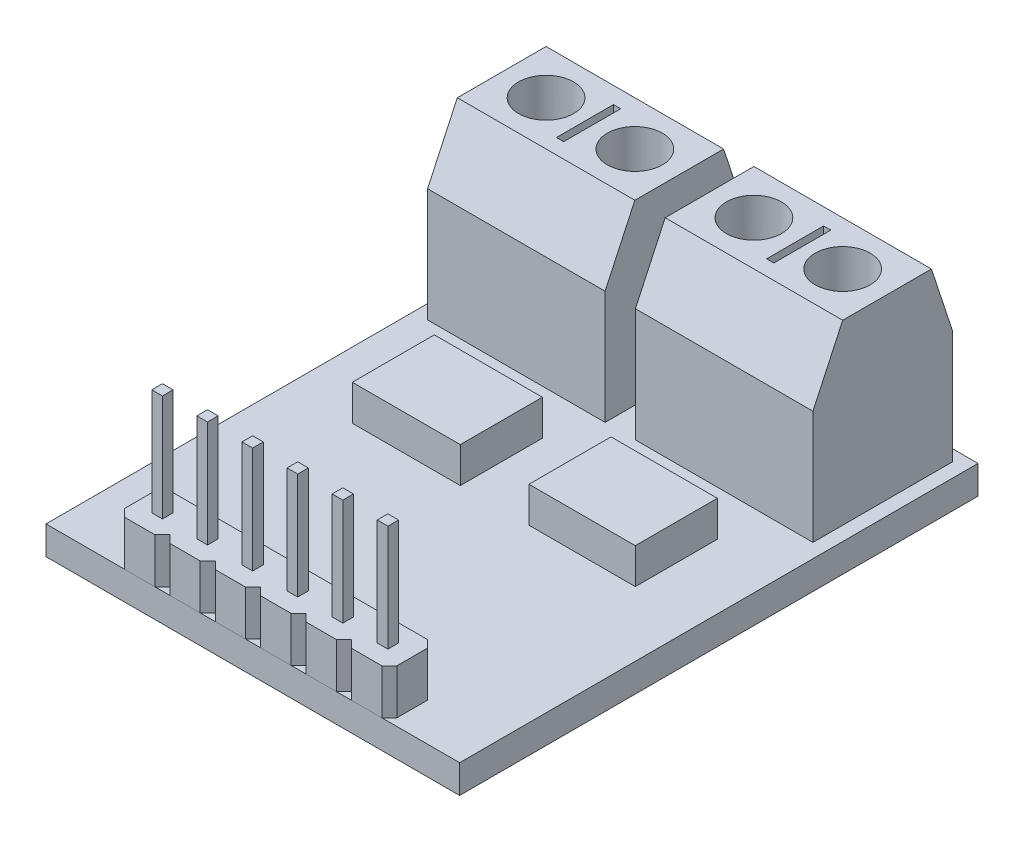
SolidWorks part; units mm, degrees
ref_plane "前视基准面" through (0, 0, 0) normal (0, 0, 1) x (1, 0, 0)
ref_plane "上视基准面" through (0, 0, 0) normal (0, 1, 0) x (1, 0, 0)
ref_plane "右视基准面" through (0, 0, 0) normal (1, 0, 0) x (0, 0, -1)
sketch "草图1" plane through (0, 0, 0) normal (0, 1, 0) x (1, 0, 0)
  line L0 (-11.65, 14.6) -> (-11.65, -14.6)
  line L1 (-11.65, 14.6) -> (11.65, 14.6)
  line L2 (-11.65, -14.6) -> (11.65, -14.6)
  line L3 (11.65, 14.6) -> (11.65, -14.6)
  line L4 (-11.65, 14.6) -> (11.65, -14.6) construction
  line L5 (-11.65, -14.6) -> (11.65, 14.6) construction
  point P1 (0, 0)
  dimension "D1" = 23.3
  dimension "D2" = 29.2
extrude "凸台-拉伸1" add sketch "草图1" along normal blind 1.6
sketch "草图2" plane through (0, 1.6, 0) normal (0, 1, 0) x (1, 0, 0)
  line L0 (0, -21.513) -> (0, -14.1561) construction
  line L1 (-4.6683, -12.0374) -> (-2.9595, -12.0374)
  line L2 (-7.2257, -12.0374) -> (-5.5169, -12.0374)
  line L3 (-7.65, -12.4617) -> (-7.65, -14.1783)
  line L4 (-7.2257, -14.6026) -> (-5.5169, -14.6026)
  line L6 (-11.65, 14.6) -> (-11.65, -14.6) construction
  line L7 (-7.2257, -12.0374) -> (-7.65, -12.4617)
  line L8 (-8.7149, -13.32) -> (-4.2245, -13.32) construction
  line L9 (-6.3713, -11.2945) -> (-6.3713, -15.2716) construction
  line L10 (-7.2257, -14.6026) -> (-7.65, -14.1783)
  line L11 (-5.5169, -14.6026) -> (-5.0926, -14.1783)
  line L12 (-5.5169, -12.0374) -> (-5.0926, -12.4617)
  line L14 (-2.9595, -12.0374) -> (-2.5352, -12.4617)
  line L15 (-2.9595, -14.6026) -> (-2.5352, -14.1783)
  line L16 (-4.6683, -14.6026) -> (-2.9595, -14.6026)
  line L17 (-4.6683, -14.6026) -> (-5.0926, -14.1783)
  line L19 (-4.6683, -12.0374) -> (-5.0926, -12.4617)
  line L20 (-2.1109, -12.0374) -> (-0.4021, -12.0374)
  line L22 (-0.4021, -12.0374) -> (0.0222, -12.4617)
  line L23 (-0.4021, -14.6026) -> (0.0222, -14.1783)
  line L24 (-2.1109, -14.6026) -> (-0.4021, -14.6026)
  line L25 (-2.1109, -14.6026) -> (-2.5352, -14.1783)
  line L27 (-2.1109, -12.0374) -> (-2.5352, -12.4617)
  line L28 (0.4465, -12.0374) -> (2.1553, -12.0374)
  line L30 (2.1553, -12.0374) -> (2.5796, -12.4617)
  line L31 (2.1553, -14.6026) -> (2.5796, -14.1783)
  line L32 (0.4465, -14.6026) -> (2.1553, -14.6026)
  line L33 (0.4465, -14.6026) -> (0.0222, -14.1783)
  line L35 (0.4465, -12.0374) -> (0.0222, -12.4617)
  line L36 (3.0039, -12.0374) -> (4.7127, -12.0374)
  line L38 (4.7127, -12.0374) -> (5.137, -12.4617)
  line L39 (4.7127, -14.6026) -> (5.137, -14.1783)
  line L40 (3.0039, -14.6026) -> (4.7127, -14.6026)
  line L41 (3.0039, -14.6026) -> (2.5796, -14.1783)
  line L43 (3.0039, -12.0374) -> (2.5796, -12.4617)
  line L44 (5.5613, -12.0374) -> (7.2701, -12.0374)
  line L45 (7.6944, -12.4617) -> (7.6944, -14.1783)
  line L46 (7.2701, -12.0374) -> (7.6944, -12.4617)
  line L47 (7.2701, -14.6026) -> (7.6944, -14.1783)
  line L48 (5.5613, -14.6026) -> (7.2701, -14.6026)
  line L49 (5.5613, -14.6026) -> (5.137, -14.1783)
  line L51 (5.5613, -12.0374) -> (5.137, -12.4617)
  line L52 (-2.5352, -12.4617) -> (-2.5352, -14.1783) [skipped]
  line L54 (0.0222, -12.4617) -> (0.0222, -14.1783) [skipped]
  line L56 (0, -12.4839) -> (0, -10.5331) construction
  line L57 (2.5796, -12.4617) -> (2.5796, -14.1783) [skipped]
  line L59 (5.137, -12.4617) -> (5.137, -14.1783) [skipped]
  line L61 (-5.0926, -12.4643) -> (-5.0926, -13.32) [skipped]
  point P3 (-5.0897, -14.1788)
  dimension "D1" = 6
  dimension "D3" = 4
  dimension "D4" = 0.6
  dimension "D5" = 135
extrude "凸台-拉伸2" add sketch "草图2" along normal blind 2.54
sketch "草图3" plane through (0, 4.14, 0) normal (0, 1, 0) x (1, 0, 0)
  line L1 (-6.6713, -13.02) -> (-6.0713, -13.02)
  line L2 (-6.6713, -13.02) -> (-6.6713, -13.62)
  line L3 (-6.6713, -13.62) -> (-6.0713, -13.62)
  line L4 (-6.0713, -13.02) -> (-6.0713, -13.62)
  line L5 (-6.3713, -11.7173) -> (-6.3713, -15.4153) construction
  line L6 (-8.2029, -13.32) -> (-4.4774, -13.32) construction
  line L7 (-5.5169, -12.0374) -> (-7.2257, -12.0374) construction
  line L8 (-7.2257, -14.6026) -> (-5.5169, -14.6026) construction
  line L9 (-7.65, -12.4617) -> (-7.65, -14.1783) construction
  dimension "D1" = 0.6
  dimension "D2" = 0.6
  dimension "D3" = 0.9787
extrude "凸台-拉伸3" add sketch "草图3" along normal blind 6
pattern_linear "阵列(线性)11" count 6 spacing 2.54 along (1, 0, 0) of "凸台-拉伸3"
sketch "草图4" plane through (0, 1.6, 0) normal (0, 1, 0) x (1, 0, 0)
  line L1 (-7.9337, 3.5592) -> (-1.8489, 3.5592)
  line L2 (-7.9337, 3.5592) -> (-7.9337, -1.0633)
  line L3 (-7.9337, -1.0633) -> (-1.8489, -1.0633)
  line L4 (-1.8489, 3.5592) -> (-1.8489, -1.0633)
  line L5 (2.0189, 3.5592) -> (8.0093, 3.5592)
  line L6 (2.0189, 3.5592) -> (2.0189, -1.0633)
  line L7 (2.0189, -1.0633) -> (8.0093, -1.0633)
  line L8 (8.0093, 3.5592) -> (8.0093, -1.0633)
extrude "凸台-拉伸4" add sketch "草图4" along normal blind 2
sketch "草图5" plane through (0, 1.6, 0) normal (0, 1, 0) x (1, 0, 0)
  line L0 (0, 19.4464) -> (0, -7.8281) construction
  line L1 (-10.8539, 13.9585) -> (-0.8539, 13.9585)
  line L2 (-10.8539, 13.9585) -> (-10.8539, 6.0985)
  line L3 (-10.8539, 6.0985) -> (-0.8539, 6.0985)
  line L4 (-0.8539, 13.9585) -> (-0.8539, 6.0985)
  line L5 (10.8539, 6.0985) -> (0.8539, 6.0985)
  line L6 (0.8539, 13.9585) -> (0.8539, 6.0985)
  line L7 (10.8539, 13.9585) -> (0.8539, 13.9585)
  line L8 (10.8539, 13.9585) -> (10.8539, 6.0985)
  dimension "D1" = 10
  dimension "D2" = 7.86
extrude "凸台-拉伸5" add sketch "草图5" along normal blind 10
sketch "草图6" plane through (-10.8539, 0, 0) normal (-1, 0, 0) x (0, 0, 1)
  line L0 (-13.9585, 8) -> (-12.7734, 11.6)
  line L1 (-13.9585, 11.6) -> (-13.9585, 1.6) construction
  line L2 (-13.9585, 11.6) -> (-6.0985, 11.6) construction
  line L3 (-12.7734, 11.6) -> (-7.7734, 11.6)
  line L4 (-7.7734, 11.6) -> (-6.0985, 8)
  line L5 (-6.0985, 11.6) -> (-6.0985, 1.6) construction
  line L6 (-6.0985, 8) -> (-4.6067, 8)
  line L7 (-4.6067, 8) -> (-4.6067, 12.7349)
  line L8 (-4.6067, 12.7349) -> (-15.2925, 12.7349)
  line L9 (-15.2925, 12.7349) -> (-15.2925, 8)
  line L10 (-15.2925, 8) -> (-13.9585, 8)
  point P13 (-12.7734, 11.6)
  dimension "D1" = 5
  dimension "D2" = 3.6
  dimension "D3" = 3.6
extrude "切除-拉伸1" cut sketch "草图6" against normal blind 28
sketch "草图7" plane through (0, 0, -13.9585) normal (0, 0, -1) x (-1, 0, 0)
  line L0 (0, -4.3965) -> (0, -1.6782) construction
  line L1 (-10.2938, 2.0196) -> (-6.2041, 2.0196)
  line L2 (10.2938, 7.4805) -> (6.2041, 7.4805)
  line L3 (10.2938, 7.4805) -> (10.2938, 2.0196)
  line L4 (10.2938, 2.0196) -> (6.2041, 2.0196)
  line L5 (6.2041, 7.4805) -> (6.2041, 2.0196)
  line L6 (5.5185, 7.4805) -> (1.4288, 7.4805)
  line L7 (5.5185, 7.4805) -> (5.5185, 2.0196)
  line L8 (5.5185, 2.0196) -> (1.4288, 2.0196)
  line L9 (1.4288, 7.4805) -> (1.4288, 2.0196)
  line L10 (-6.2041, 7.4805) -> (-6.2041, 2.0196)
  line L11 (-10.2938, 7.4805) -> (-6.2041, 7.4805)
  line L12 (-10.2938, 7.4805) -> (-10.2938, 2.0196)
  line L13 (-5.5185, 2.0196) -> (-1.4288, 2.0196)
  line L14 (-1.4288, 7.4805) -> (-1.4288, 2.0196)
  line L15 (-5.5185, 7.4805) -> (-1.4288, 7.4805)
  line L16 (-5.5185, 7.4805) -> (-5.5185, 2.0196)
extrude "切除-拉伸2" cut sketch "草图7" against normal blind 6
sketch "草图8" plane through (0, 11.6, 0) normal (0, 1, 0) x (1, 0, 0)
  line L0 (-12.9018, 10.2734) -> (16.4174, 10.2734) construction
  line L1 (10.8539, 12.7734) -> (0.8539, 12.7734) construction
  line L2 (0.8539, 7.7734) -> (10.8539, 7.7734) construction
  line L3 (-10.8539, 12.7734) -> (-10.8539, 7.7734) construction
  line L4 (-6.1233, 11.838) -> (-5.7149, 11.838)
  line L5 (-6.1233, 11.838) -> (-6.1233, 8.6257)
  line L6 (-6.1233, 8.6257) -> (-5.7149, 8.6257)
  line L7 (-5.7149, 11.838) -> (-5.7149, 8.6257)
  line L8 (-0.8539, 6.0985) -> (-0.8539, 13.9585) construction
  line L9 (0, 17.9632) -> (0, 2.0922) construction
  line L10 (6.1233, 8.6257) -> (5.7149, 8.6257)
  line L11 (5.7149, 11.838) -> (5.7149, 8.6257)
  line L12 (6.1233, 11.838) -> (5.7149, 11.838)
  line L13 (6.1233, 11.838) -> (6.1233, 8.6257)
  circle A0 centre (-8.3539, 10.2734) radius 1.55
  circle A1 centre (-3.3539, 10.2734) radius 1.55
  circle A2 centre (8.3539, 10.2734) radius 1.55
  circle A3 centre (3.3539, 10.2734) radius 1.55
  dimension "D1" = 3.1
  dimension "D2" = 2.5
  dimension "D3" = 2.5
extrude "切除-拉伸3" cut sketch "草图8" against normal blind 6
